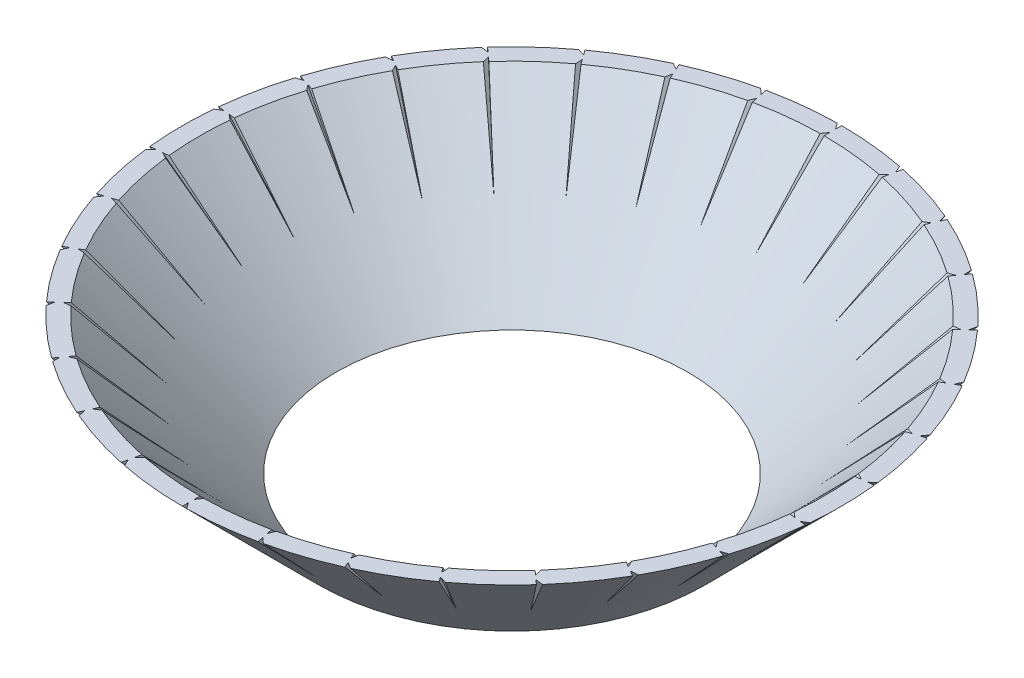
SolidWorks part; units mm, degrees
revolve "Base-Revolve" add sketch "Sketch1" angle 360 about L0
sketch "Sketch1" plane through (0, 0, 0) normal (1, 0, 0) x (0, 0, -1)
  line L0 (0, -30) -> (0, 30) construction
  line L1 (8.5, 0) -> (15.1, 6.6)
  line L2 (8.5, 0) -> (9.3485, 0)
  line L3 (9.3485, 0) -> (15.9485, 6.6)
  line L4 (15.1, 6.6) -> (15.9485, 6.6)
  dimension "D1" = 45
  dimension "InsideDia" = 17
  dimension "OutsideDia" = 30.2
  dimension "Thickness" = 0.6
ref_plane "Plane1" through (0, 0, 0) normal (0, 0, 1) x (1, 0, 0)
ref_plane "Plane2" through (0, 0, 0) normal (0, 1, 0) x (1, 0, 0)
ref_plane "Plane3" through (0, 0, 0) normal (1, 0, 0) x (0, 0, -1)
sketch "Sketch3" plane through (0, 0, 0) normal (1, 0, 0) x (0, 0, -1)
  line L1 (11.8, 3.3) -> (16.4649, 7.6)
  line L3 (8.5, 0) -> (15.1, 6.6) construction
  line L4 (15.9485, 6.6) -> (-15.9485, 6.6) construction
  point P4 (15.38, 6.6)
  dimension "D1" = 3.3
  dimension "D2" = 15.38
  dimension "D3" = 1
ref_plane "Plane4" through (0, 3.3, -11.8) normal (0, 0.6778, -0.7353) x (-1, 0, 0)
sketch "Sketch5" plane through (0, 3.3, -11.8) normal (0, 0.6778, -0.7353) x (-1, 0, 0)
  line L0 (0, 0) -> (0, 1)
  line L1 (0, 1) -> (1, 1)
  line L2 (1, 1) -> (0, 0)
  dimension "D1" = 1
  dimension "D2" = 1
sweep "Cut-Sweep1" cut profiles "Sketch5" path "Sketch3"
ref_plane "Plane6" through (0, 3.3, -12.6485) normal (0, -0.7071, -0.7071) x (1, 0, 0)
ref_plane "Plane7" through (0, -4.4621, -4.4621) normal (0, -0.7071, -0.7071) x (1, 0, 0)
mirror "Mirror2" about plane through (0, -4.4621, -4.4621) normal (0, -0.7071, -0.7071) of "Cut-Sweep1"
pattern_circular "CirPattern1" count 30 over 360 about axis through (0, 0, 0) along (0, 1, 0) of "Mirror2", "Cut-Sweep1"
equation "\"D1@Sketch3\" = ( \"OutsideDia@Sketch1\" - \"InsideDia@Sketch1\" )  / 4"
equation "\"D2@Sketch3\" = \"OutsideDia@Sketch1\" / 2 + (sqr(\"Thickness@Sketch1\" * \"Thickness@Sketch1\" + \"Thickness@Sketch1\" * \"Thickness@Sketch1\") * .33)"
equation "\"D1@Plane7\" = \"Thickness@Sketch1\" / 2"
